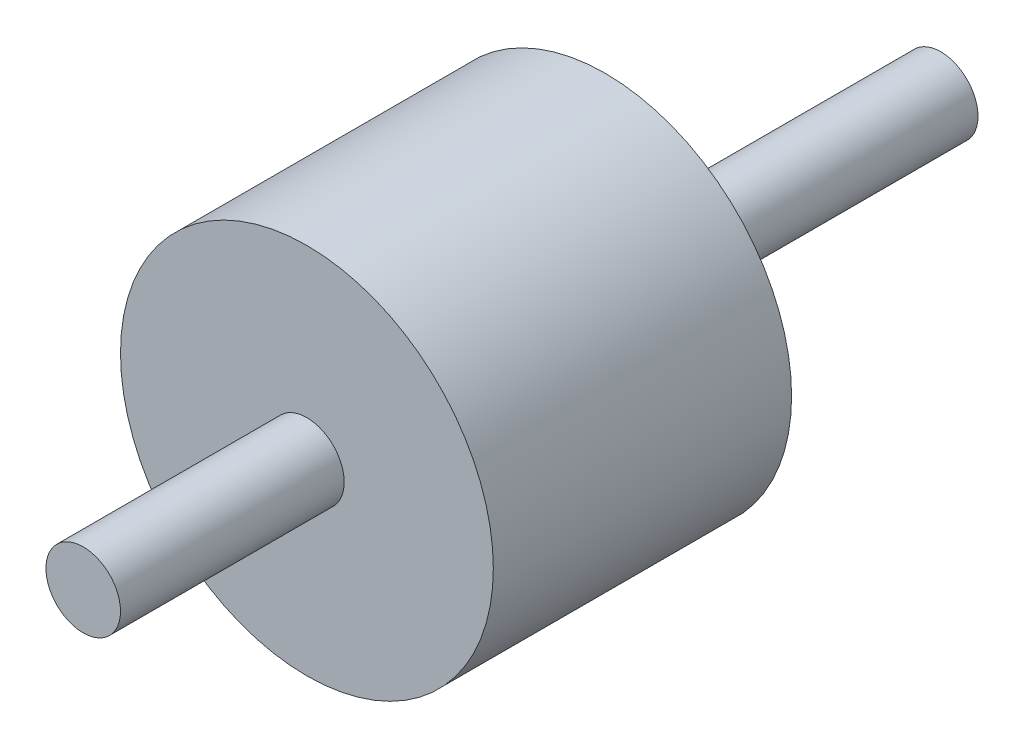
SolidWorks part; units mm, degrees
ref_plane "Front Plane" through (0, 0, 0) normal (0, 0, 1) x (1, 0, 0)
ref_plane "Top Plane" through (0, 0, 0) normal (0, 1, 0) x (1, 0, 0)
ref_plane "Right Plane" through (0, 0, 0) normal (1, 0, 0) x (0, 0, -1)
sketch "Sketch2" plane through (0, 0, 0) normal (0, 0, 1) x (1, 0, 0)
  circle A0 centre (0, 0) radius 5
  dimension "D1" = 10
extrude "Boss-Extrude1" add sketch "Sketch2" along normal blind 115
ref_plane "Plane1" through (0, 0, 85) normal (0, 0, 1) x (1, 0, 0)
sketch "Sketch3" plane through (0, 0, 85) normal (0, 0, 1) x (1, 0, 0)
  circle A0 centre (0, 0) radius 25
  dimension "D1" = 50
extrude "Boss-Extrude2" add sketch "Sketch3" against normal blind 40
ref_plane "Plane2" through (0, 0, 35) normal (0, 0, -1) x (-1, 0, 0)
sketch "Sketch4" plane through (0, 0, 35) normal (0, 0, -1) x (-1, 0, 0)
  circle A0 centre (0, 0) radius 7.5
  dimension "D1" = 15
extrude "Boss-Extrude3" add sketch "Sketch4" against normal blind 10
